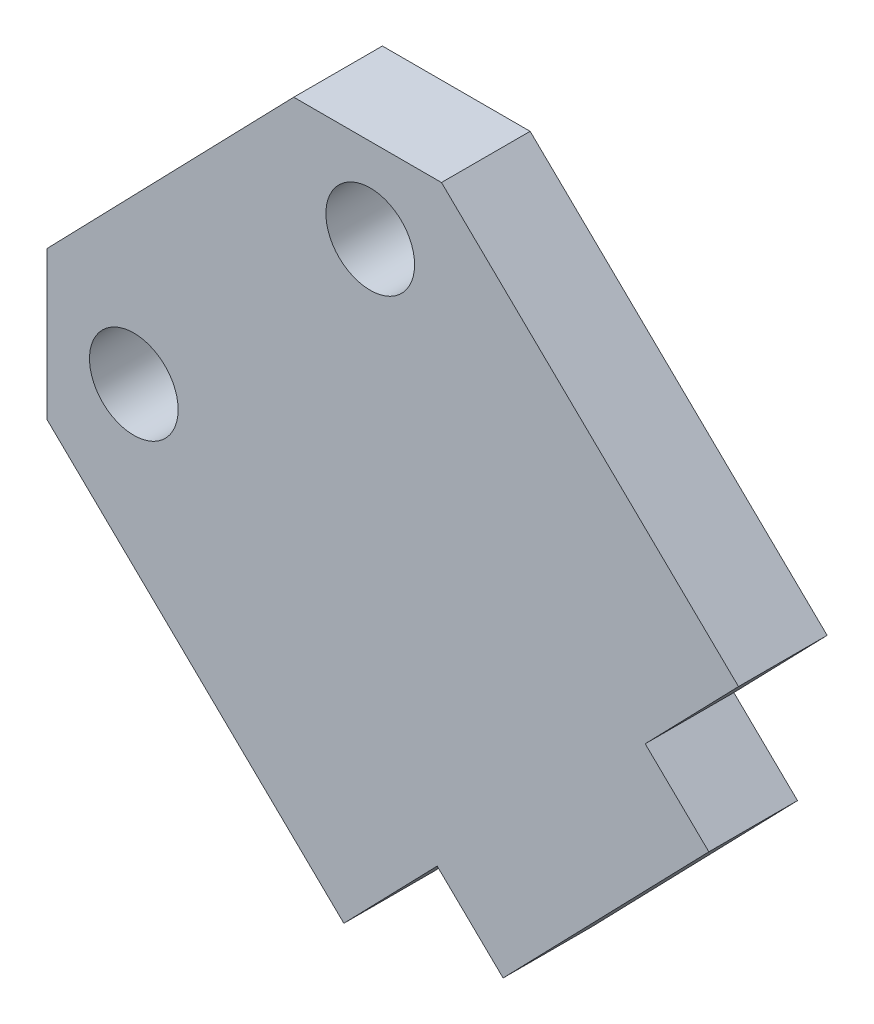
SolidWorks part; units mm, degrees
ref_plane "Plan de face" through (0, 0, 0) normal (0, 0, 1) x (1, 0, 0)
ref_plane "Plan de dessus" through (0, 0, 0) normal (0, 1, 0) x (1, 0, 0)
ref_plane "Plan de droite" through (0, 0, 0) normal (1, 0, 0) x (0, 0, -1)
sketch "Esquisse1" plane through (0, 0, 0) normal (0, 0, 1) x (1, 0, 0)
  line L0 (68.1847, 459.8724) -> (149.1786, 401.2209) construction
  line L6 (-10.9431, -5.75) -> (-2.5894, 2.8648)
  line L7 (-2.5894, 2.8648) -> (2.4106, 2.8648)
  line L10 (0, 0) -> (3.0179, 0) construction
  line L20 (2.4106, 2.8648) -> (12.4613, -6.8812)
  line L22 (-0.8925, -20.496) -> (-10.9431, -10.75)
  line L23 (-10.9431, -10.75) -> (-10.9431, -5.75)
  line L24 (-8, -8.25) -> (0, 0) construction
  line L25 (-8, -8.25) -> (-10.9431, -5.75) construction
  line L26 (0, 0) -> (-2.5894, 2.8648) construction
  line L27 (-8, -8.25) -> (-10.9431, -10.75) construction
  line L28 (-0.8925, -20.496) -> (2.2646, -17.2403)
  line L29 (2.2646, -17.2403) -> (4.4964, -19.4044)
  line L30 (4.4964, -19.4044) -> (11.4579, -12.2254)
  line L31 (11.4579, -12.2254) -> (9.3042, -10.137)
  line L32 (9.3042, -10.137) -> (12.4613, -6.8812)
  circle A0 centre (0, 0) radius 1.5
  circle A1 centre (-8, -8.25) radius 1.5
extrude "Boss.-Extru.2" add sketch "Esquisse1" along normal blind 3
